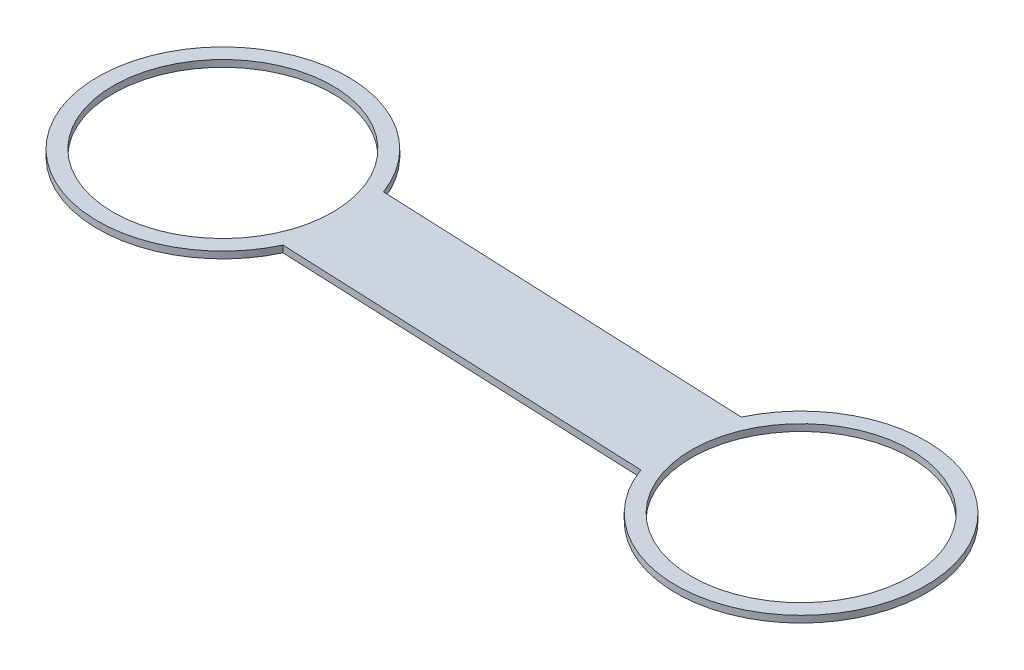
SolidWorks part; units mm, degrees
ref_plane "Front Plane" through (0, 0, 0) normal (0, 0, 1) x (1, 0, 0)
ref_plane "Top Plane" through (0, 0, 0) normal (0, 1, 0) x (1, 0, 0)
ref_plane "Right Plane" through (0, 0, 0) normal (1, 0, 0) x (0, 0, -1)
sketch "Sketch1" plane through (0, 0, 0) normal (0, 1, 0) x (1, 0, 0)
  line L1 (34.7245, 12.7755) -> (145.341, 8)
  line L2 (33.4954, -15.7181) -> (144.0331, -20.4012)
  circle A0 centre (0, 0) radius 32.4358
  arc A1 (34.7245, 12.7755) -> (33.4954, -15.7181) centre (0, 0) ccw
  circle A2 centre (178.811, -7.7721) radius 32.4358
  arc A3 (144.0331, -20.4012) -> (145.341, 8) centre (178.811, -7.7721) ccw
extrude "Boss-Extrude1" add sketch "Sketch1" along normal blind 2
